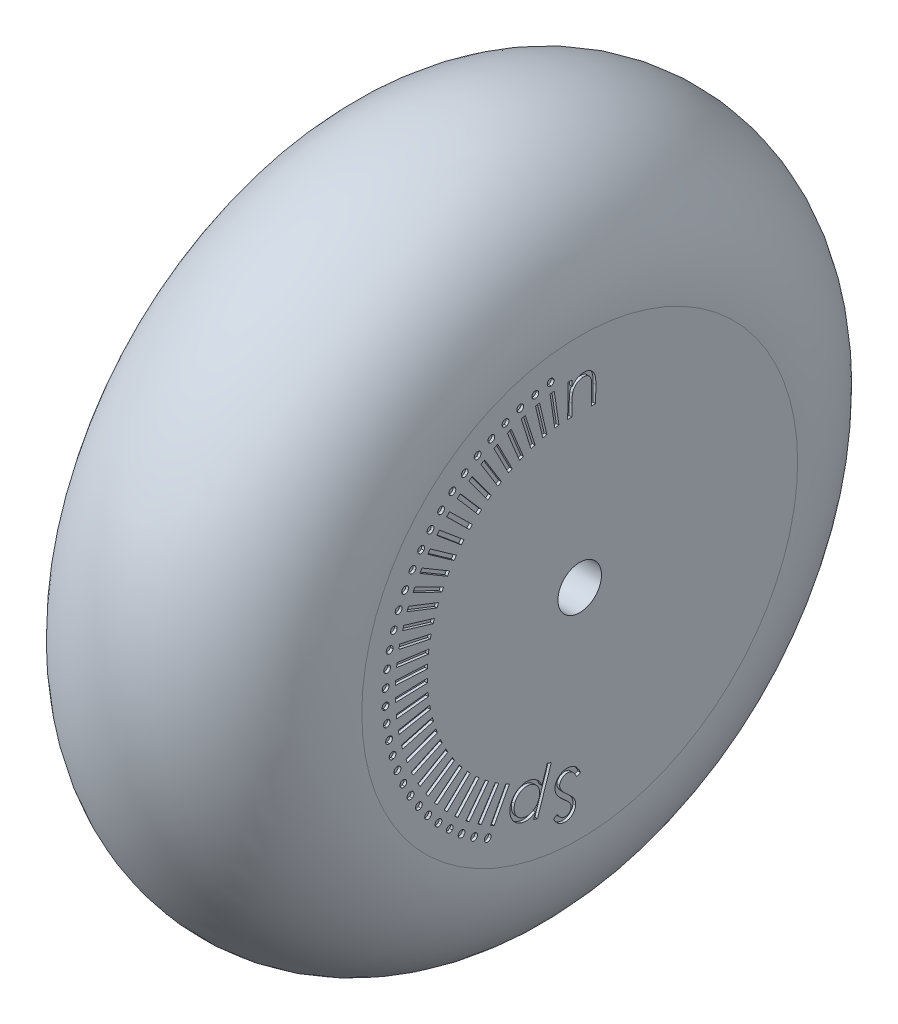
SolidWorks part; units mm, degrees
ref_plane "Front Plane" through (0, 0, 0) normal (0, 0, 1) x (1, 0, 0)
ref_plane "Top Plane" through (0, 0, 0) normal (0, 1, 0) x (1, 0, 0)
ref_plane "Right Plane" through (0, 0, 0) normal (1, 0, 0) x (0, 0, -1)
sketch "Sketch1" plane through (0, 0, 0) normal (0, 0, 1) x (1, 0, 0)
  line L0 (-38.1, 0) -> (38.1, 0) construction
  line L1 (-38.1, 6.35) -> (38.1, 6.35)
  line L2 (-38.1, 6.35) -> (-38.1, 63.5)
  line L3 (38.1, 63.5) -> (38.1, 6.35)
  arc A0 (-38.1, 63.5) -> (38.1, 63.5) centre (0, 63.5) cw
  point P4 (0, 0)
  point P7 (0, 6.35)
  dimension "D3" = 101.6
  dimension "D1" = 76.2
  dimension "D2" = 6.35
revolve "Revolve1" add sketch "Sketch1" angle 360 about L0
sketch "Sketch2" plane through (38.1, 0, 0) normal (1, 0, 0) x (0, 0, -1)
  circle A2 centre (0, 0) radius 44.45
  circle A3 centre (0, 0) radius 44.45 construction
  text T0 "Spiiiiiiiiiiiiiiiiiiiiiiiiiiiiiiiin\r\n" font "Century Gothic" height 12.7
  dimension "D1" = 19.05
extrude "Cut-Extrude1" cut sketch "Sketch2" against normal blind 0.7937
